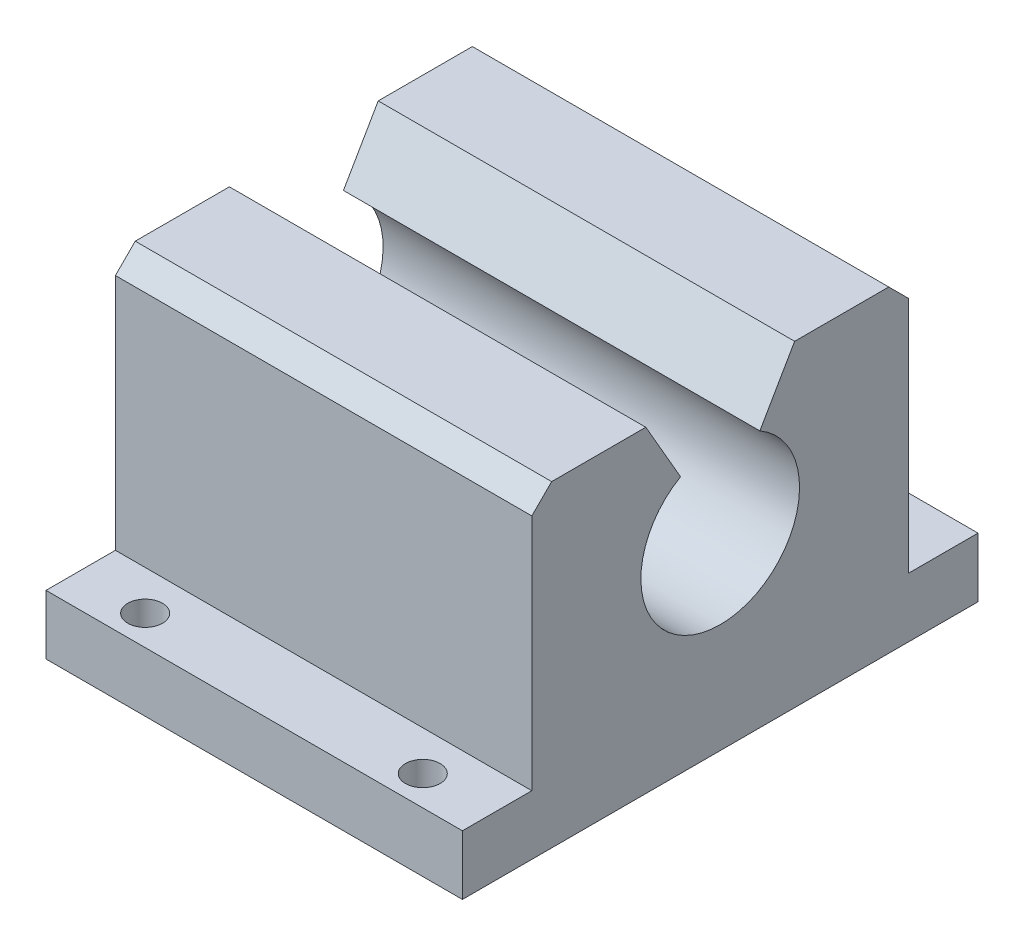
SolidWorks part; units mm, degrees
material "PW50:5:Ar:0:-1:C1:1:2:3:Re:11:"
ref_plane "front" through (0, 0, 0) normal (0, 0, 1) x (1, 0, 0)
ref_plane "top" through (0, 0, 0) normal (0, 1, 0) x (1, 0, 0)
ref_plane "side" through (0, 0, 0) normal (1, 0, 0) x (0, 0, -1)
sketch "Sketch1" plane through (0, 0, 0) normal (1, 0, 0) x (0, 0, -1)
  line L0 (0, 0) -> (0, 82.55) construction
  line L1 (-41.275, 0) -> (41.275, 0)
  line L2 (41.275, 0) -> (41.275, 9.525)
  line L3 (41.275, 9.525) -> (30.1625, 9.525)
  line L4 (30.1625, 9.525) -> (30.1625, 50.8)
  line L5 (-30.1625, 50.8) -> (30.1625, 50.8)
  line L7 (-30.1625, 9.525) -> (-30.1625, 50.8)
  line L8 (-41.275, 9.525) -> (-30.1625, 9.525)
  line L9 (-41.275, 0) -> (-41.275, 9.525)
  circle A1 centre (0, 30.1625) radius 12.7
  point P14 (0, 0)
  dimension "D2" = 30.1625
  dimension "D3" = 25.4
  dimension "D1" = 82.55
  dimension "D4" = 50.8
  dimension "D7" = 9.525
extrude "Base-Extrude" add sketch "Sketch1" along normal blind 66.675
sketch "Sketch2" plane through (0, 9.525, 0) normal (0, 1, 0) x (-1, 0, 0)
  line L0 (-66.675, 41.275) -> (-66.675, 30.1625) construction
  line L1 (-66.675, 41.275) -> (0, 41.275) construction
  circle A0 centre (-55.5625, 36.5125) radius 2.7781
  dimension "D1" = 5.5562
  dimension "D2" = 11.1125
  dimension "D3" = 4.7625
extrude "Cut-Extrude1" cut sketch "Sketch2" against normal through all
pattern_linear "LPattern1" count 2 spacing 44.45 along (-1, 0, 0) count 2 spacing 73.025 along (0, 0, -1) of "Cut-Extrude1"
sketch "Sketch3" plane through (66.675, 0, 0) normal (1, 0, 0) x (0, 0, -1)
  line L0 (0, 30.1625) -> (0, 55.5587) construction
  line L1 (11.9151, 50.8) -> (-11.9151, 50.8)
  line L2 (-30.1625, 50.8) -> (30.1625, 50.8) construction
  line L3 (11.9151, 50.8) -> (0, 30.1625)
  line L4 (-11.9151, 50.8) -> (0, 30.1625)
  point P8 (0, 50.8)
  dimension "D1" = 60
extrude "Cut-Extrude2" cut sketch "Sketch3" against normal through all
chamfer "Chamfer1" distance 3.175 angle 45 2 edges at (33.3375, 50.8, 30.1625) (33.3375, 50.8, -30.1625)
